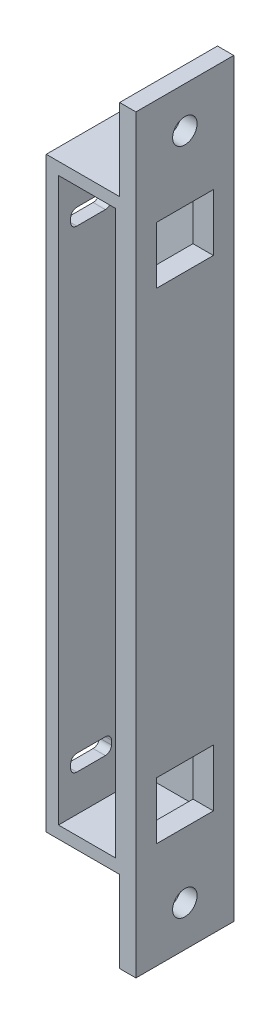
SolidWorks part; units mm, degrees
ref_plane "Front Plane" through (0, 0, 0) normal (0, 0, 1) x (1, 0, 0)
ref_plane "Top Plane" through (0, 0, 0) normal (0, 1, 0) x (1, 0, 0)
ref_plane "Right Plane" through (0, 0, 0) normal (1, 0, 0) x (0, 0, -1)
sketch "Sketch1" plane through (0, 0, 0) normal (0, 0, 1) x (1, 0, 0)
  line L1 (0, 0) -> (11, 0)
  line L2 (0, 0) -> (0, 72)
  line L3 (0, 72) -> (11, 72)
  line L4 (11, 0) -> (11, 72)
  dimension "D1" = 72
  dimension "D2" = 11
extrude "Boss-Extrude1" add sketch "Sketch1" along normal blind 12
sketch "Sketch2" plane through (11, 0, 0) normal (1, 0, 0) x (0, 0, -1)
  line L0 (-12, 36) -> (0, 36) construction
  line L1 (-12, 72) -> (0, 72)
  line L2 (-12, 72) -> (-12, 82)
  line L3 (-12, 82) -> (0, 82)
  line L4 (0, 72) -> (0, 82)
  line L5 (-12, 0) -> (-12, 72) construction
  line L6 (0, 0) -> (0, 72) construction
  line L7 (-12, -10) -> (0, -10)
  line L8 (0, 0) -> (0, -10)
  line L9 (-12, 0) -> (0, 0)
  line L10 (-12, 0) -> (-12, -10)
  circle A0 centre (-6, 77) radius 1.5
  circle A1 centre (-6, -5) radius 1.5
  point P18 (-12, 77)
  point P20 (-6, 82)
  dimension "D3" = 3
  dimension "D1" = 10
extrude "Boss-Extrude2" add sketch "Sketch2" against normal blind 2
sketch "Sketch3" plane through (11, 0, 0) normal (1, 0, 0) x (0, 0, -1)
  line L0 (-12, 36) -> (0, 36) construction
  line L1 (-12, -10) -> (-12, 82) construction
  line L2 (0, -10) -> (0, 82) construction
  line L3 (-6, 82) -> (-6, -10) construction
  line L4 (-9.5, 69) -> (-2.5, 69)
  line L5 (-9.5, 69) -> (-9.5, 62)
  line L6 (-9.5, 62) -> (-2.5, 62)
  line L7 (-2.5, 69) -> (-2.5, 62)
  line L8 (0, 82) -> (-12, 82) construction
  line L9 (-12, -10) -> (0, -10) construction
  line L10 (-9.5, 10) -> (-2.5, 10)
  line L11 (-2.5, 3) -> (-2.5, 10)
  line L12 (-9.5, 3) -> (-2.5, 3)
  line L13 (-9.5, 3) -> (-9.5, 10)
  point P20 (-9.5, 65.5)
  point P21 (-9.5, 6.5)
  dimension "D1" = 7
  dimension "D2" = 7
  dimension "D3" = 59
extrude "Cut-Extrude1" cut sketch "Sketch3" against normal blind 3
sketch "Sketch4" plane through (0, 0, 12) normal (0, 0, 1) x (1, 0, 0)
  line L0 (0, 36) -> (11, 36) construction
  line L1 (1.5, 70.5) -> (8.5, 70.5)
  line L2 (1.5, 70.5) -> (1.5, 1.5)
  line L3 (1.5, 1.5) -> (8.5, 1.5)
  line L4 (8.5, 70.5) -> (8.5, 1.5)
  line L5 (0, 72) -> (0, 0) construction
  line L6 (11, -10) -> (11, 82) construction
  line L7 (5, 70.5) -> (5, 1.5) construction
  dimension "D1" = 69
  dimension "D2" = 7
  dimension "D3" = 6
extrude "Cut-Extrude2" cut sketch "Sketch4" against normal blind 10.5
sketch "Sketch5" plane through (0, 0, 0) normal (-1, 0, 0) x (0, 0, 1)
  line L0 (12, 72) -> (12, 0) construction
  line L1 (6.25, 66) -> (9.75, 66)
  line L2 (5.5, 65.25) -> (5.5, 64.75)
  line L3 (6.25, 64) -> (9.75, 64)
  line L4 (10.5, 65.25) -> (10.5, 64.75)
  line L5 (12, 72) -> (0, 72) construction
  line L6 (0, 36) -> (12, 36) construction
  line L7 (0, 72) -> (0, 0) construction
  line L8 (6.25, 8) -> (9.75, 8)
  line L9 (10.5, 6.75) -> (10.5, 7.25)
  line L10 (6.25, 6) -> (9.75, 6)
  line L11 (5.5, 6.75) -> (5.5, 7.25)
  arc A0 (10.5, 64.75) -> (9.75, 64) centre (9.75, 64.75) cw
  arc A1 (10.5, 65.25) -> (9.75, 66) centre (9.75, 65.25) ccw
  arc A2 (5.5, 64.75) -> (6.25, 64) centre (6.25, 64.75) ccw
  arc A3 (5.5, 65.25) -> (6.25, 66) centre (6.25, 65.25) cw
  arc A4 (10.5, 7.25) -> (9.75, 8) centre (9.75, 7.25) ccw
  arc A5 (10.5, 6.75) -> (9.75, 6) centre (9.75, 6.75) cw
  arc A6 (5.5, 7.25) -> (6.25, 8) centre (6.25, 7.25) cw
  arc A7 (5.5, 6.75) -> (6.25, 6) centre (6.25, 6.75) ccw
  point P10 (10.5, 64)
  point P13 (10.5, 66)
  point P18 (5.5, 66)
  dimension "D5" = 0.75
  dimension "D1" = 1.5
  dimension "D2" = 5
  dimension "D3" = 8
  dimension "D4" = 2
extrude "Cut-Extrude3" cut sketch "Sketch5" against normal up to surface (1.5 mm away) up to face at (1.5, 36, 6.75)
